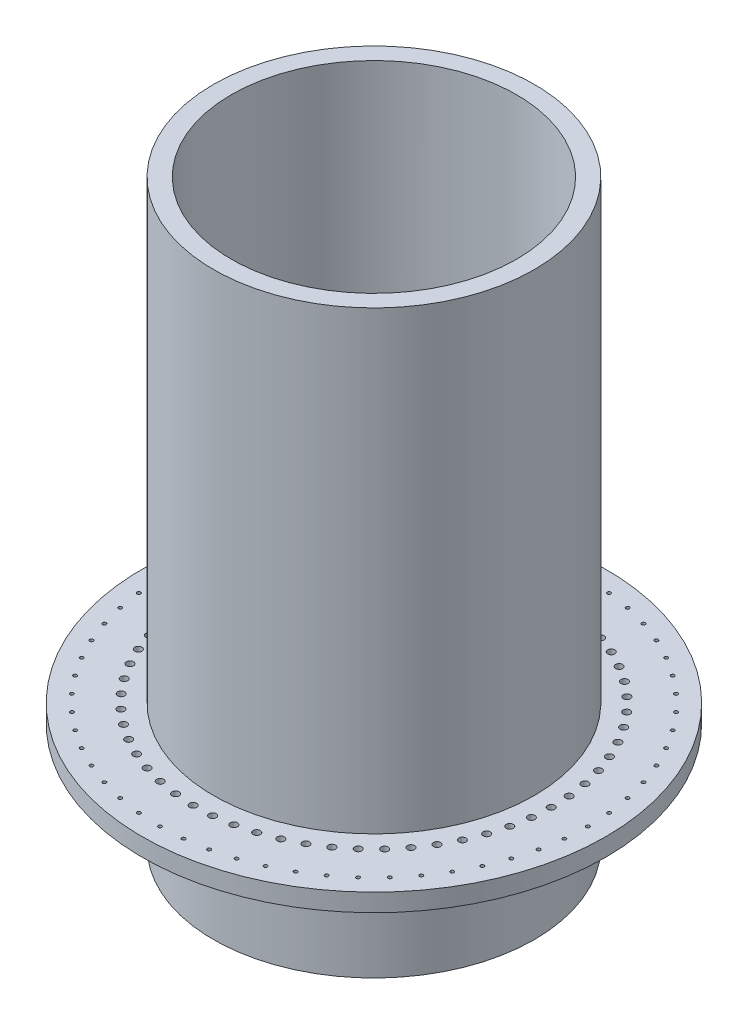
SolidWorks part; units mm, degrees
ref_plane "Front Plane" through (0, 0, 0) normal (0, 0, 1) x (1, 0, 0)
ref_plane "Top Plane" through (0, 0, 0) normal (0, 1, 0) x (1, 0, 0)
ref_plane "Right Plane" through (0, 0, 0) normal (1, 0, 0) x (0, 0, -1)
sketch "Sketch1" plane through (0, 0, 0) normal (0, 0, 1) x (1, 0, 0)
  line L0 (0, -777.6582) -> (0, 38105.2507) construction
  line L1 (-20, 2.5) -> (-20, 80)
  line L4 (20, 80) -> (20, 0)
  line L5 (-20, 0) -> (-22.5, 0)
  line L6 (-22.5, 0) -> (-22.5, 15)
  line L7 (-22.5, 81.382) -> (-20, 81.382)
  line L8 (20, 0) -> (22.5, 0)
  line L9 (22.5, 0) -> (22.5, 15)
  line L10 (-20, 80) -> (-20, 81.382)
  line L11 (22.5, 81.382) -> (20, 81.382)
  line L12 (20, 80) -> (20, 81.382)
  line L13 (-22.5, 15) -> (-32.5, 15)
  line L14 (-32.5, 15) -> (-32.5, 17.5)
  line L15 (-32.5, 17.5) -> (-22.5, 17.5)
  line L16 (32.5, 15) -> (32.5, 17.5)
  line L17 (32.5, 17.5) -> (22.5, 17.5)
  line L18 (22.5, 15) -> (32.5, 15)
  line L19 (-22.5, 17.5) -> (-22.5, 81.382)
  line L20 (22.5, 17.5) -> (22.5, 81.382)
  line L21 (-20, 0) -> (-11.5451, 0)
  line L22 (-11.5451, 0) -> (-7.2361, -8.618)
  line L23 (-20, 2.5) -> (-10, 2.5)
  line L24 (-10, 2.5) -> (-5, -7.5)
  line L25 (-7.2361, -8.618) -> (-5, -8.618)
  line L26 (-5, -8.618) -> (-5, -7.5)
  point P12 (0, 82.5)
  dimension "D1" = 80
  dimension "D2" = 20
  dimension "D3" = 2.5
  dimension "D4" = 15
  dimension "D5" = 10
  dimension "D6" = 10
  dimension "D7" = 10
  dimension "D8" = 2.5
  dimension "D9" = 2.5
  dimension "D10" = 90
  dimension "D11" = 2.2361
revolve "Revolve1" add sketch "Sketch1" angle 360 about L0
sketch "Sketch3" plane through (0, 0, 0) normal (0, -1, 0) x (1, 0, 0)
  line L0 (0, 22.5) -> (0, -22.5) construction
  line L1 (-22.5, 0) -> (22.5, 0) construction
  line L2 (-19.9609, 1.25) -> (-13.9893, 1.25)
  line L3 (19.9609, 1.25) -> (13.9893, 1.25)
  line L4 (-1.25, 19.9609) -> (-1.25, 13.9893)
  line L5 (1.25, 19.9609) -> (1.25, 13.9893)
  line L6 (19.9609, -1.25) -> (13.9893, -1.25)
  line L7 (-19.9609, -1.25) -> (-13.9893, -1.25)
  line L8 (-1.25, -19.9609) -> (-1.25, -13.9893)
  line L9 (1.25, -19.9609) -> (1.25, -13.9893)
  circle A0 centre (0, 0) radius 22.5 construction
  circle A1 centre (0, 0) radius 22.5 construction
  arc A2 (-19.9609, -1.25) -> (-1.25, -19.9609) centre (0, 0) ccw
  arc A3 (-13.9893, -1.25) -> (-1.25, -13.9893) centre (0, 0) ccw
  circle A4 centre (0, 0) radius 11.5451 construction
  arc A5 (1.25, -13.9893) -> (13.9893, -1.25) centre (0, 0) ccw
  arc A6 (1.25, -19.9609) -> (19.9609, -1.25) centre (0, 0) ccw
  arc A7 (13.9893, 1.25) -> (1.25, 13.9893) centre (0, 0) ccw
  arc A8 (19.9609, 1.25) -> (1.25, 19.9609) centre (0, 0) ccw
  arc A9 (-1.25, 19.9609) -> (-19.9609, 1.25) centre (0, 0) ccw
  arc A10 (-1.25, 13.9893) -> (-13.9893, 1.25) centre (0, 0) ccw
  dimension "D1" = 40
  dimension "D2" = 2.5
  dimension "D3" = 1.25
  dimension "D4" = 2.5
extrude "Cut-Extrude1" cut sketch "Sketch3" against normal blind 10
sketch "Sketch4" plane through (0, 15, 0) normal (0, -1, 0) x (1, 0, 0)
  circle A0 centre (0, 0) radius 27.5 construction
  circle A1 centre (-30, 0) radius 0.25
  circle A2 centre (-25, 2.3785) radius 0.5
  circle A3 centre (0, 30) radius 0.25
  circle A4 centre (2.3785, 25) radius 0.5
  circle A5 centre (0, 0) radius 27.5 construction
  circle A6 centre (30, 0) radius 0.25
  circle A7 centre (25, -2.3785) radius 0.5
  circle A8 centre (0, 0) radius 27.5 construction
  circle A9 centre (0, -30) radius 0.25
  circle A10 centre (-2.3785, -25) radius 0.5
  circle A11 centre (0, 0) radius 27.5 construction
  point P25 (0, 0)
  dimension "D3" = 55
  dimension "D4" = 0.5
  dimension "D5" = 1
  dimension "D1" = 30
  dimension "D2" = 25
  dimension "D6" = 4
extrude "Cut-Extrude2" cut sketch "Sketch4" against normal blind 10 contours A7 | A1 | A2 | A4 | A3 | A6 | A9 | A10
pattern_circular "CirPattern1" count 15 over 360 about axis through (0, 0, 0) along (0, 1, 0) of "Cut-Extrude2"
